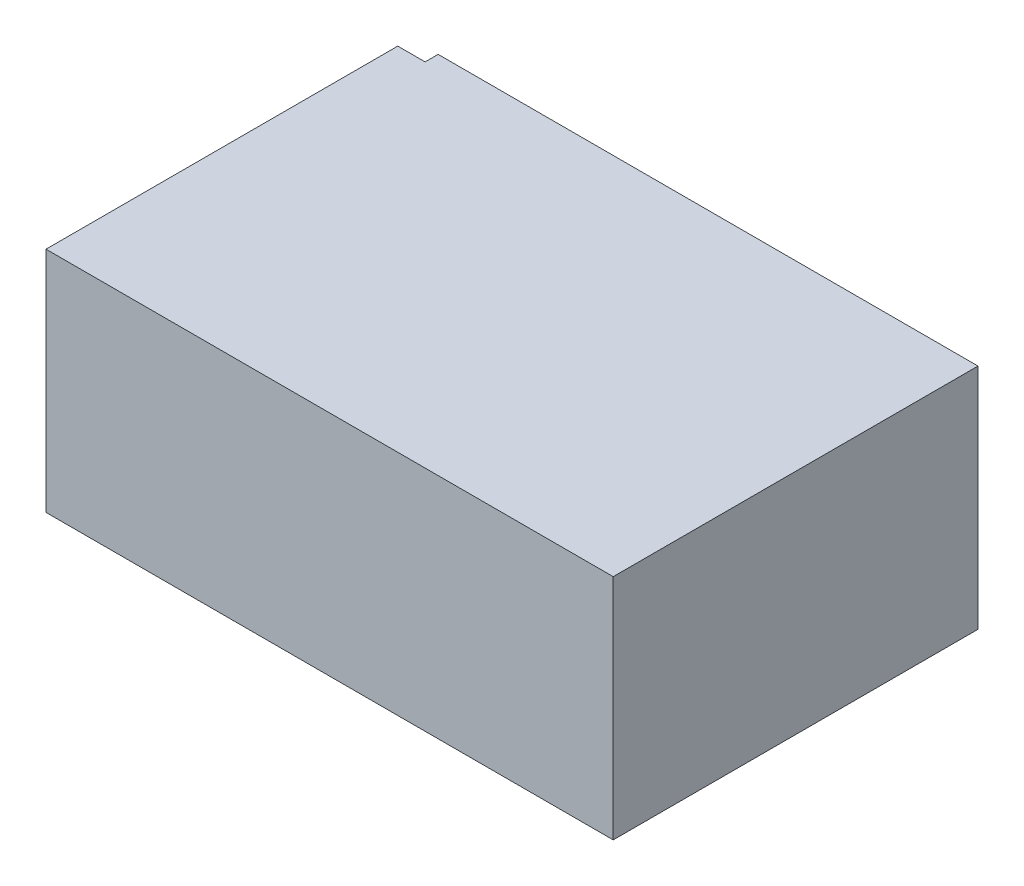
SolidWorks part; units mm, degrees
ref_plane "정면" through (0, 0, 0) normal (0, 0, 1) x (1, 0, 0)
ref_plane "윗면" through (0, 0, 0) normal (0, 1, 0) x (1, 0, 0)
ref_plane "우측면" through (0, 0, 0) normal (1, 0, 0) x (0, 0, -1)
sketch "스케치8" plane through (0, 0, 0) normal (0, 1, 0) x (1, 0, 0)
  line L1 (-87.075, 56) -> (87.075, 56)
  line L2 (-87.075, 56) -> (-87.075, -56)
  line L3 (-87.075, -56) -> (87.075, -56)
  line L4 (87.075, 56) -> (87.075, -56)
  line L5 (-87.075, 56) -> (87.075, -56) construction
  line L6 (-87.075, -56) -> (87.075, 56) construction
  point P0 (0, 0)
  dimension "D1" = 174.15
  dimension "D2" = 112
extrude "보스-돌출3" add sketch "스케치8" along normal blind 70
sketch "스케치9" plane through (-87.075, 0, 0) normal (-1, 0, 0) x (0, 0, 1)
  line L1 (-56, 52.5) -> (-52, 52.5)
  line L2 (-56, 52.5) -> (-56, 17.5)
  line L3 (-56, 17.5) -> (-52, 17.5)
  line L4 (-52, 52.5) -> (-52, 17.5)
  line L6 (-56, 70) -> (56, 70) construction
  dimension "D1" = 4
  dimension "D2" = 35
  dimension "D3" = 17.5
sketch "스케치10" plane through (0, 0, -56) normal (0, 0, -1) x (-1, 0, 0)
  line L0 (-87.075, 0) -> (87.075, 0) construction
  line L1 (-87.075, 70) -> (78.6753, 70)
  line L2 (-87.075, 70) -> (-87.075, 0)
  line L3 (-87.075, 0) -> (78.6753, 0)
  line L4 (78.6753, 70) -> (78.6753, 0)
  line L5 (87.075, 52.5) -> (87.075, 17.5) construction
  line L6 (87.075, 52.5) -> (78.6753, 52.5)
  line L7 (87.075, 52.5) -> (87.075, 17.5)
  line L8 (87.075, 17.5) -> (78.6753, 17.5)
  line L9 (78.6753, 52.5) -> (78.6753, 17.5)
  line M1 (-87.075, 0) -> (87.075, 0)
  line M2 (87.075, 0) -> (87.075, 70)
  line M3 (87.075, 70) -> (-87.075, 70)
extrude "컷-돌출4" cut sketch "스케치10" against normal blind 4 contours L6 L4 M2 M3 | L8 L4 M2 M1
